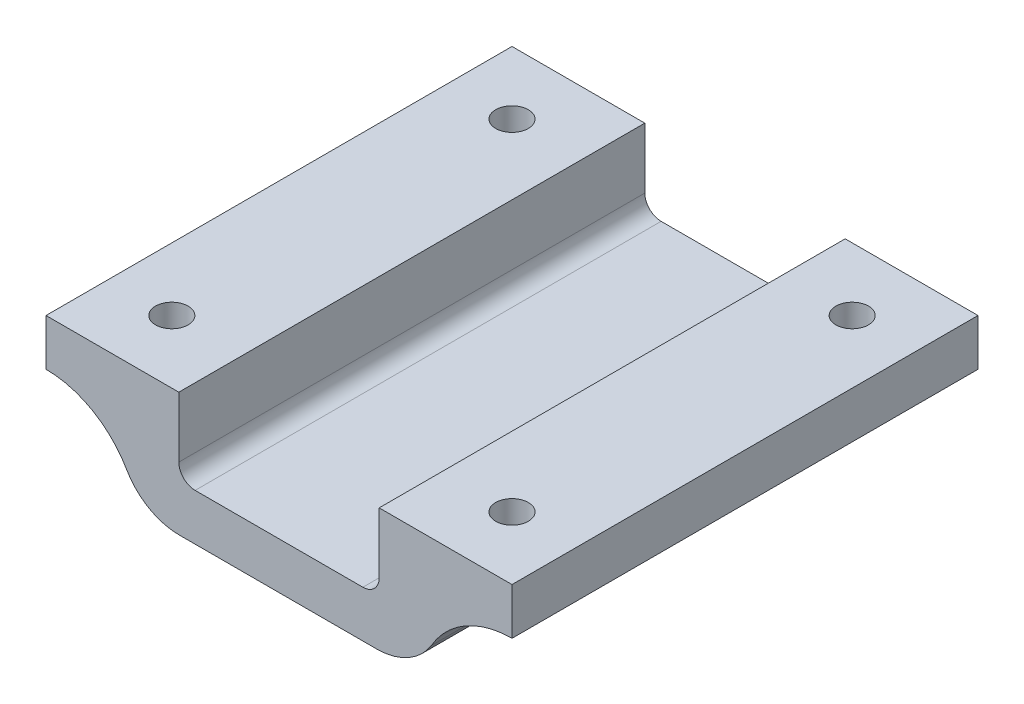
SolidWorks part; units mm, degrees
ref_plane "Front Plane" through (0, 0, 0) normal (0, 0, 1) x (1, 0, 0)
ref_plane "Top Plane" through (0, 0, 0) normal (0, 1, 0) x (1, 0, 0)
ref_plane "Right Plane" through (0, 0, 0) normal (1, 0, 0) x (0, 0, -1)
sketch "Sketch1" plane through (0, 0, 0) normal (0, 0, 1) x (1, 0, 0)
  line L0 (15, 13.2239) -> (35, 13.2239) construction
  line L1 (50, 10.2246) -> (50, 5.2246)
  line L2 (35.75, 10.2246) -> (50, 10.2246)
  line L3 (35.75, 3.7246) -> (35.75, 10.2246)
  line L4 (15, 22.2239) -> (15, 4.2239)
  line L5 (16, 3.2239) -> (34, 3.2239)
  line L6 (35, 4.2239) -> (35, 22.2239)
  line L7 (34, 23.2239) -> (16, 23.2239)
  line L8 (15, 22.2239) -> (15, 4.2239) construction
  line L9 (16, 3.2239) -> (34, 3.2239) construction
  line L10 (35, 4.2239) -> (35, 22.2239) construction
  line L11 (34, 23.2239) -> (16, 23.2239) construction
  line L12 (16, 1.9746) -> (34, 1.9746)
  line L13 (14.25, 10.2246) -> (14.25, 3.7246)
  line L14 (0, 10.2246) -> (14.25, 10.2246)
  line L15 (0, 5.2246) -> (0, 10.2246)
  line L16 (37.0096, 28.7233) -> (12.9904, 28.7233)
  line L17 (0, 21.2233) -> (0, 16.2233)
  line L18 (0, 16.2233) -> (14.25, 16.2233)
  line L19 (14.25, 16.2233) -> (14.25, 22.7233)
  line L20 (16, 24.4733) -> (34, 24.4733)
  line L21 (35.75, 22.7233) -> (35.75, 16.2233)
  line L22 (35.75, 16.2233) -> (50, 16.2233)
  line L23 (50, 16.2233) -> (50, 21.2233)
  line L24 (37.0096, 28.7233) -> (12.9904, 28.7233) construction
  line L25 (0, 21.2233) -> (0, 16.2233) construction
  line L26 (0, 16.2233) -> (14.25, 16.2233) construction
  line L27 (14.25, 16.2233) -> (14.25, 22.7233) construction
  line L28 (16, 24.4733) -> (34, 24.4733) construction
  line L29 (35.75, 22.7233) -> (35.75, 16.2233) construction
  line L30 (35.75, 16.2233) -> (50, 16.2233) construction
  line L31 (50, 16.2233) -> (50, 21.2233) construction
  line L33 (14.2894, -3.0254) -> (35.7106, -3.0254)
  arc A1 (41.3397, 0.2246) -> (50, 5.2246) centre (50, -4.7754) cw
  arc A2 (35.75, 3.7246) -> (34, 1.9746) centre (34, 3.7246) cw
  arc A3 (16, 1.9746) -> (14.25, 3.7246) centre (16, 3.7246) cw
  arc A4 (16, 23.2239) -> (15, 22.2239) centre (16, 22.2239) ccw
  arc A5 (15, 4.2239) -> (16, 3.2239) centre (16, 4.2239) ccw
  arc A6 (34, 3.2239) -> (35, 4.2239) centre (34, 4.2239) ccw
  arc A7 (35, 22.2239) -> (34, 23.2239) centre (34, 22.2239) ccw
  arc A8 (16, 23.2239) -> (15, 22.2239) centre (16, 22.2239) ccw construction
  arc A9 (15, 4.2239) -> (16, 3.2239) centre (16, 4.2239) ccw construction
  arc A10 (34, 3.2239) -> (35, 4.2239) centre (34, 4.2239) ccw construction
  arc A11 (35, 22.2239) -> (34, 23.2239) centre (34, 22.2239) ccw construction
  arc A12 (0, 5.2246) -> (8.6603, 0.2246) centre (0, -4.7754) cw
  arc A14 (12.9904, 28.7233) -> (8.6603, 26.2233) centre (12.9904, 23.7233) ccw
  arc A15 (0, 21.2233) -> (8.6603, 26.2233) centre (0, 31.2233) ccw
  arc A16 (16, 24.4733) -> (14.25, 22.7233) centre (16, 22.7233) ccw
  arc A17 (35.75, 22.7233) -> (34, 24.4733) centre (34, 22.7233) ccw
  arc A18 (41.3397, 26.2233) -> (50, 21.2233) centre (50, 31.2233) ccw
  arc A19 (41.3397, 26.2233) -> (37.0096, 28.7233) centre (37.0096, 23.7233) ccw
  arc A20 (12.9904, 28.7233) -> (8.6603, 26.2233) centre (12.9904, 23.7233) ccw construction
  arc A21 (0, 21.2233) -> (8.6603, 26.2233) centre (0, 31.2233) ccw construction
  arc A22 (16, 24.4733) -> (14.25, 22.7233) centre (16, 22.7233) ccw construction
  arc A23 (35.75, 22.7233) -> (34, 24.4733) centre (34, 22.7233) ccw construction
  arc A24 (41.3397, 26.2233) -> (50, 21.2233) centre (50, 31.2233) ccw construction
  arc A25 (41.3397, 26.2233) -> (37.0096, 28.7233) centre (37.0096, 23.7233) ccw construction
  arc A26 (8.6603, 0.2246) -> (14.2894, -3.0254) centre (14.2894, 3.4746) ccw
  arc A27 (35.7106, -3.0254) -> (41.3397, 0.2246) centre (35.4411, 3.9414) ccw
  point P52 (25, -3.0254)
  point P53 (25, 1.9746)
  dimension "D3" = 5
  dimension "D1" = 0
  dimension "D2" = 0
extrude "Boss-Extrude1" add sketch "Sketch1" against normal blind 50
sketch "Sketch2" plane through (0, -3.0254, 0) normal (0, -1, 0) x (1, 0, 0)
  circle A16 centre (6.75, -43.25) radius 1.75 construction
  circle A17 centre (43.25, -43.25) radius 1.75 construction
  circle A18 centre (6.75, -6.75) radius 1.75 construction
  circle A19 centre (43.25, -6.75) radius 1.75 construction
  circle A20 centre (6.75, -43.25) radius 1.75
  circle A21 centre (43.25, -43.25) radius 1.75
  circle A22 centre (6.75, -6.75) radius 1.75
  circle A23 centre (43.25, -6.75) radius 1.75
extrude "Cut-Extrude1" cut sketch "Sketch2" against normal through all
sketch "Sketch3" plane through (0, -3.0254, 0) normal (0, -1, 0) x (1, 0, 0)
  line L0 (25, 0) -> (25, -50) construction
  line L1 (9.75, -5.0179) -> (6.75, -3.2859)
  line L2 (6.75, -3.2859) -> (3.75, -5.0179)
  line L3 (3.75, -5.0179) -> (3.75, -8.4821)
  line L4 (3.75, -8.4821) -> (6.75, -10.2141)
  line L5 (6.75, -10.2141) -> (9.75, -8.4821)
  line L6 (9.75, -8.4821) -> (9.75, -5.0179)
  line L7 (6.7708, -39.786) -> (3.7605, -41.4999)
  line L8 (3.7605, -41.4999) -> (3.7396, -44.964)
  line L9 (3.7396, -44.964) -> (6.7292, -46.714)
  line L10 (6.7292, -46.714) -> (9.7395, -45.0001)
  line L11 (9.7395, -45.0001) -> (9.7604, -41.536)
  line L12 (9.7604, -41.536) -> (6.7708, -39.786)
  line L13 (14.2894, 0) -> (35.7106, 0) construction
  line L14 (35.7106, -50) -> (14.2894, -50) construction
  line L15 (25, -50) -> (0, -25) construction
  line L16 (0, -50) -> (0, 0) construction
  line L17 (0, -25) -> (50, -25) construction
  line L18 (50, -50) -> (50, 0) construction
  line L19 (40.2396, -41.536) -> (43.2292, -39.786)
  line L20 (40.2605, -45.0001) -> (40.2396, -41.536)
  line L21 (43.2708, -46.714) -> (40.2605, -45.0001)
  line L22 (46.2604, -44.964) -> (43.2708, -46.714)
  line L23 (46.2395, -41.4999) -> (46.2604, -44.964)
  line L24 (43.2292, -39.786) -> (46.2395, -41.4999)
  line L25 (40.25, -8.4821) -> (40.25, -5.0179)
  line L26 (43.25, -10.2141) -> (40.25, -8.4821)
  line L27 (46.25, -8.4821) -> (43.25, -10.2141)
  line L28 (46.25, -5.0179) -> (46.25, -8.4821)
  line L29 (43.25, -3.2859) -> (46.25, -5.0179)
  line L30 (40.25, -5.0179) -> (43.25, -3.2859)
  circle A0 centre (6.75, -6.75) radius 3 construction
  circle A1 centre (6.75, -43.25) radius 3 construction
  circle A2 centre (43.25, -43.25) radius 3 construction
  circle A3 centre (43.25, -6.75) radius 3 construction
  dimension "D1" = 6
extrude "Cut-Extrude2" cut sketch "Sketch3" against normal up to vertex (8.25 mm away) up to point (50, 5.2246, 0)
